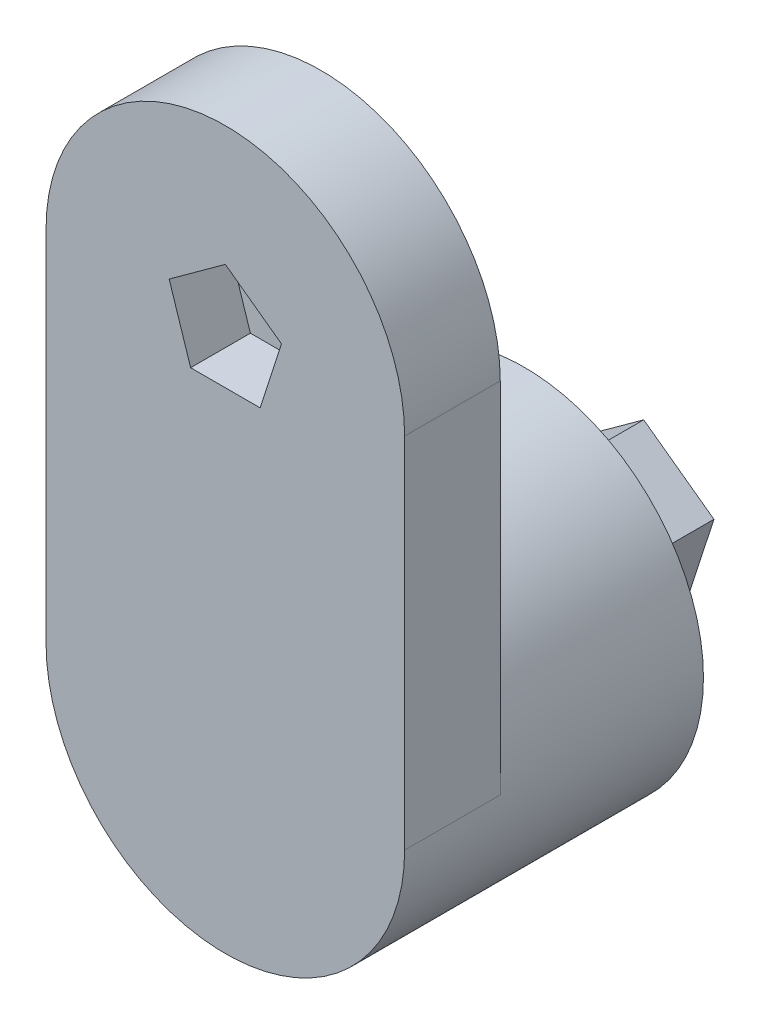
SolidWorks part; units mm, degrees
ref_plane "정면" through (0, 0, 0) normal (0, 0, 1) x (1, 0, 0)
ref_plane "윗면" through (0, 0, 0) normal (0, 1, 0) x (1, 0, 0)
ref_plane "우측면" through (0, 0, 0) normal (1, 0, 0) x (0, 0, -1)
sketch "스케치1" plane through (0, 0, 0) normal (0, 0, 1) x (1, 0, 0)
  line L0 (-15, 15) -> (-15, -15)
  line L1 (15, -15) -> (15, 15)
  arc A1 (-15, -15) -> (15, -15) centre (0, -15) ccw
  arc A2 (15, 15) -> (-15, 15) centre (0, 15) ccw
  point P8 (0, 0)
  point P13 (0, 0)
  point P14 (0, 0)
  point P16 (0.979, 15)
  point P17 (0.506, 15)
  point P18 (0, 0)
  dimension "D3" = 15
  dimension "D1" = 15
  dimension "D2" = 30
extrude "보스-돌출1" add sketch "스케치1" along normal blind 8
sketch "스케치2" plane through (0, 0, 8) normal (0, 0, 1) x (1, 0, 0)
  line L1 (0, 19.9423) -> (-4.7004, 16.5272)
  line L2 (-4.7004, 16.5272) -> (-2.905, 11.0016)
  line L3 (-2.905, 11.0016) -> (2.905, 11.0016)
  line L4 (2.905, 11.0016) -> (4.7004, 16.5272)
  line L5 (4.7004, 16.5272) -> (0, 19.9423)
  circle A0 centre (0, 15) radius 3.9984 construction
  point P1 (0, 0)
  dimension "D1" = 5.81
extrude "컷-돌출1" cut sketch "스케치2" against normal blind 5
sketch "스케치3" plane through (0, 0, 0) normal (0, 0, -1) x (-1, 0, 0)
  circle A0 centre (0, -15) radius 15
extrude "보스-돌출2" add sketch "스케치3" along normal blind 17
sketch "스케치4" plane through (0, 0, -17) normal (0, 0, -1) x (-1, 0, 0)
  line L1 (0, -8.8197) -> (-5.8779, -13.0902)
  line L2 (-5.8779, -13.0902) -> (-3.6327, -20)
  line L3 (-3.6327, -20) -> (3.6327, -20)
  line L4 (3.6327, -20) -> (5.8779, -13.0902)
  line L5 (5.8779, -13.0902) -> (0, -8.8197)
  circle A0 centre (0, -15) radius 5 construction
  dimension "D1" = 10
extrude "보스-돌출3" add sketch "스케치4" along normal blind 10
